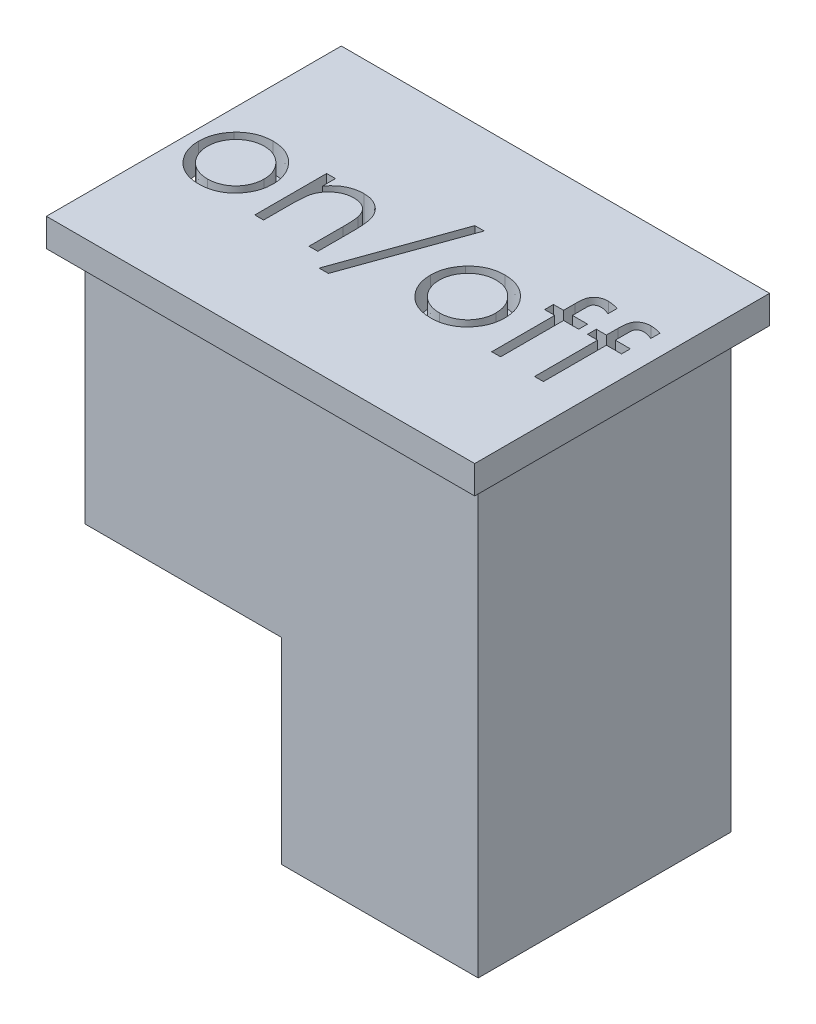
SolidWorks part; units mm, degrees
ref_plane "Alzado" through (0, 0, 0) normal (0, 0, 1) x (1, 0, 0)
ref_plane "Planta" through (0, 0, 0) normal (0, 1, 0) x (1, 0, 0)
ref_plane "Vista lateral" through (0, 0, 0) normal (1, 0, 0) x (0, 0, -1)
sketch "Croquis1" plane through (0, 0, 0) normal (0, 1, 0) x (1, 0, 0)
  line L1 (-7, -4.5) -> (7, -4.5)
  line L2 (-7, -4.5) -> (-7, 4.5)
  line L3 (-7, 4.5) -> (7, 4.5)
  line L4 (7, -4.5) -> (7, 4.5)
  line L5 (-7, -4.5) -> (7, 4.5) construction
  line L6 (-7, 4.5) -> (7, -4.5) construction
  point P0 (0, 0)
  dimension "D1" = 14
  dimension "D2" = 9
extrude "Saliente-Extruir1" add sketch "Croquis1" along normal blind 8.55
sketch "Croquis2" plane through (0, 0, 0) normal (0, 1, 0) x (1, 0, 0)
  line L1 (-7.625, -5.25) -> (7.625, -5.25)
  line L2 (-7.625, -5.25) -> (-7.625, 5.25)
  line L3 (-7.625, 5.25) -> (7.625, 5.25)
  line L4 (7.625, -5.25) -> (7.625, 5.25)
  line L5 (-7.625, -5.25) -> (7.625, 5.25) construction
  line L6 (-7.625, 5.25) -> (7.625, -5.25) construction
  point P0 (0, 0)
  dimension "D1" = 10.5
  dimension "D2" = 15.25
extrude "Saliente-Extruir2" add sketch "Croquis2" along normal blind 1 from surface at 8.55 starting at face at (0, 8.55, 0)
sketch "Croquis3" plane through (0, 0, 0) normal (0, 1, 0) x (1, 0, 0)
  line L0 (-7, -4.5) -> (7, -4.5) construction
  line L1 (7, 4.5) -> (0, 4.5)
  line L2 (7, 4.5) -> (7, -4.5)
  line L3 (7, -4.5) -> (0, -4.5)
  line L4 (0, 4.5) -> (0, -4.5)
  dimension "D1" = 7
extrude "Saliente-Extruir3" add sketch "Croquis3" against normal blind 7
sketch "Croquis4" plane through (0, 9.55, 0) normal (0, 1, 0) x (1, 0, 0)
  text T0 "on/off"
  point P4 (1.0443, -2.3002)
  dimension "D1" = 7.5
  dimension "D2" = 1.5
extrude "Cortar-Extruir1" cut sketch "Croquis4" against normal blind 1
